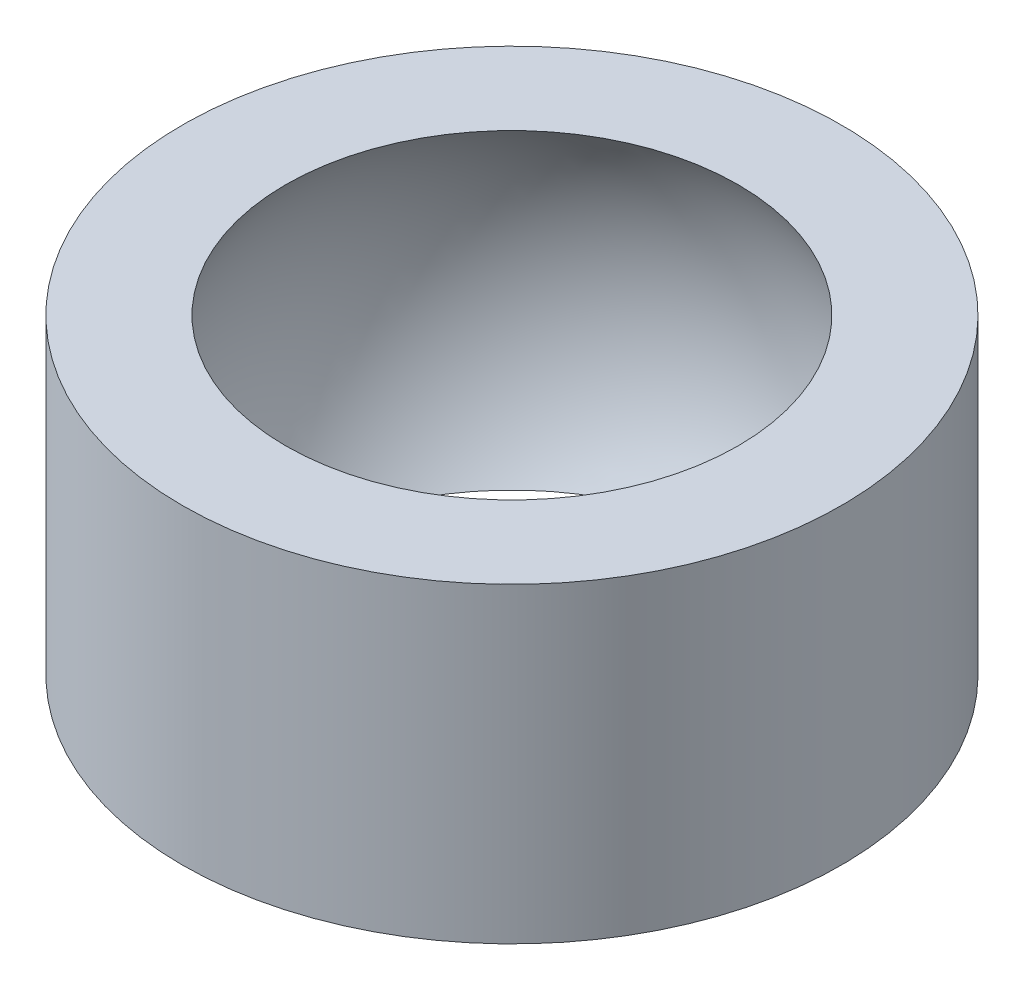
SolidWorks part; units mm, degrees
ref_plane "Alzado" through (0, 0, 0) normal (0, 0, 1) x (1, 0, 0)
ref_plane "Planta" through (0, 0, 0) normal (0, 1, 0) x (1, 0, 0)
ref_plane "Vista lateral" through (0, 0, 0) normal (1, 0, 0) x (0, 0, -1)
sketch "Croquis1" plane through (0, 0, 0) normal (0, 0, 1) x (1, 0, 0)
  line L0 (0, 0) -> (9.525, 0) construction
  line L1 (9.525, 0) -> (9.525, 4.5)
  line L2 (9.525, 4.5) -> (6.5386, 4.5)
  line L3 (-9.525, 4.5) -> (-9.525, -4.5) construction
  line L4 (-9.525, -4.5) -> (-6.5386, -4.5) construction
  line L5 (9.525, -4.5) -> (9.525, 0)
  line L6 (0, 0) -> (-9.525, 0) construction
  line L7 (6.5386, -4.5) -> (9.525, -4.5)
  line L8 (-6.5386, 4.5) -> (-9.525, 4.5) construction
  line L9 (0, 0) -> (0, -3.1673) construction
  arc A0 (-6.5386, 4.5) -> (-6.5386, -4.5) centre (0, 0) ccw construction
  arc A1 (6.5386, -4.5) -> (6.5386, 4.5) centre (0, 0) ccw
  dimension "D1" = 15.875
  dimension "D2" = 19.05
  dimension "D3" = 9
revolve "Revolución1" add sketch "Croquis1" angle 360 about L9
